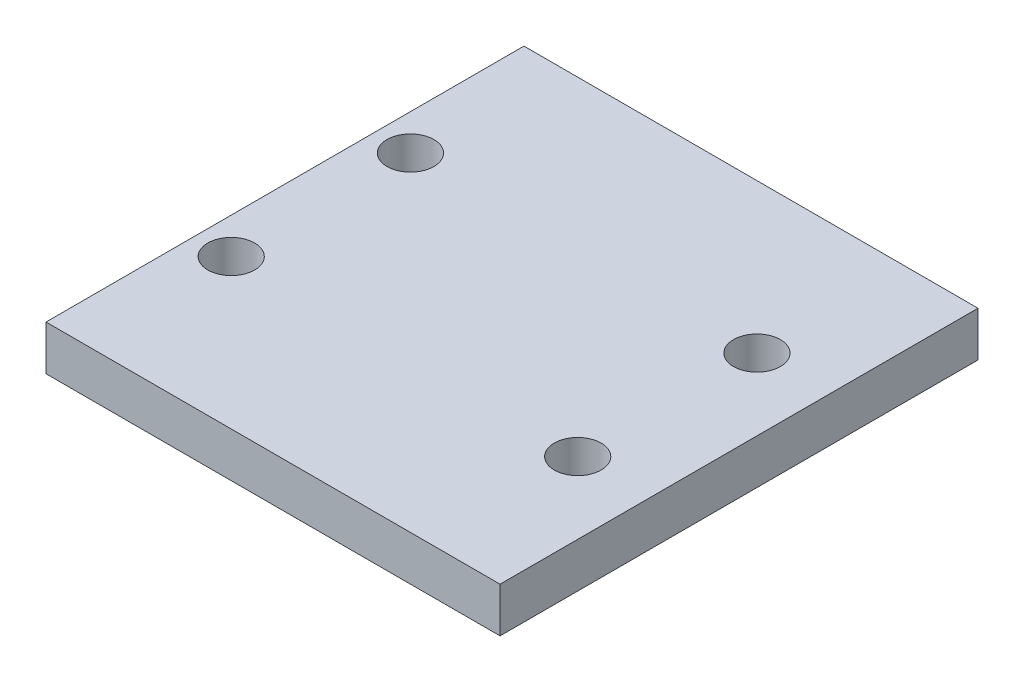
SolidWorks part; units mm, degrees
ref_plane "Front Plane" through (0, 0, 0) normal (0, 0, 1) x (1, 0, 0)
ref_plane "Top Plane" through (0, 0, 0) normal (0, 1, 0) x (1, 0, 0)
ref_plane "Right Plane" through (0, 0, 0) normal (1, 0, 0) x (0, 0, -1)
sketch "Sketch1" plane through (0, 0, 0) normal (0, 1, 0) x (1, 0, 0)
  line L1 (0, 0) -> (48.26, 0)
  line L2 (0, 0) -> (0, 50.8)
  line L3 (0, 50.8) -> (48.26, 50.8)
  line L4 (48.26, 0) -> (48.26, 50.8)
  dimension "D1" = 48.26
  dimension "D2" = 50.8
extrude "Boss-Extrude1" add sketch "Sketch1" along normal blind 4.7625
sketch "Sketch2" plane through (0, 4.7625, 0) normal (0, 1, 0) x (1, 0, 0)
  line L0 (0, 50.8) -> (0, 0) construction
  line L1 (0, 0) -> (48.26, 0) construction
  line L4 (0, 25.4) -> (48.26, 25.4) construction
  line L5 (48.26, 0) -> (48.26, 50.8) construction
  circle A0 centre (3.81, 15.875) radius 2.4892
  circle A1 centre (40.64, 15.875) radius 2.4892
  circle A2 centre (40.64, 34.925) radius 2.4892
  circle A3 centre (3.81, 34.925) radius 2.4892
  point P20 (25.4, 50.8)
  dimension "D1" = 4.9784
  dimension "D2" = 3.81
  dimension "D3" = 15.875
  dimension "D4" = 7.62
  dimension "D5" = 15.875
extrude "Cut-Extrude1" cut sketch "Sketch2" against normal blind 4.7625
